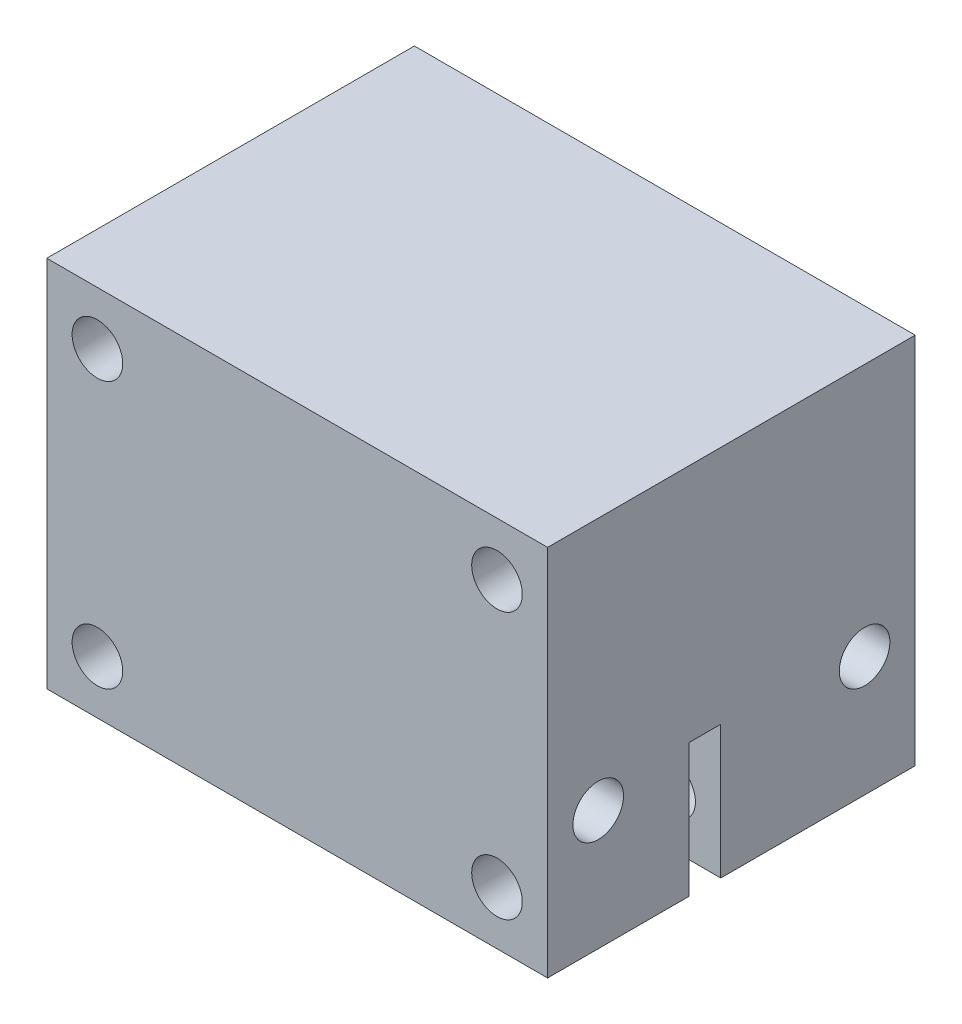
SolidWorks part; units mm, degrees
material "PBT 一般用途"
ref_plane "前视基准面" through (0, 0, 0) normal (0, 0, 1) x (1, 0, 0)
ref_plane "上视基准面" through (0, 0, 0) normal (0, 1, 0) x (1, 0, 0)
ref_plane "右视基准面" through (0, 0, 0) normal (1, 0, 0) x (0, 0, -1)
sketch "草图1" plane through (0, 0, 0) normal (0, 0, 1) x (1, 0, 0)
  line L0 (18.8, 28) -> (18.8, 0) construction
  line L1 (0, 0) -> (37.6, 0)
  line L2 (0, 0) -> (0, 28)
  line L3 (0, 28) -> (37.6, 28)
  line L4 (37.6, 0) -> (37.6, 28)
  line L6 (3.8, 4) -> (33.8, 4) construction
  line L7 (3.8, 4) -> (3.8, 24) construction
  line L8 (3.8, 24) -> (33.8, 24) construction
  line L9 (33.8, 4) -> (33.8, 24) construction
  line L10 (3.8, 4) -> (33.8, 24) construction
  line L11 (3.8, 24) -> (33.8, 4) construction
  circle A0 centre (3.8, 24) radius 1.9
  circle A1 centre (33.8, 24) radius 1.9
  circle A2 centre (33.8, 4) radius 1.9
  circle A3 centre (3.8, 4) radius 1.9
  point P7 (18.8, 14)
  dimension "D3" = 20
  dimension "D5" = 3.8
  dimension "D1" = 28
  dimension "D2" = 37.6
  dimension "D4" = 30
extrude "凸台-拉伸1" add sketch "草图1" along normal blind 27.6
sketch "草图2" plane through (37.6, 0, 0) normal (1, 0, 0) x (0, 0, -1)
  line L0 (-13.8, 28) -> (-13.8, 0) construction
  line L1 (-27.6, 28) -> (0, 28) construction
  line L2 (-27.6, 0) -> (0, 0) construction
  line L3 (-23.8, 9) -> (-3.8, 9) construction
  line L4 (-27.6, 0) -> (-27.6, 28) construction
  line L5 (-17, 0) -> (-14.6, 0)
  line L6 (-17, 0) -> (-17, 10)
  line L7 (-17, 10) -> (-14.6, 10)
  line L8 (-14.6, 0) -> (-14.6, 10)
  circle A0 centre (-23.8, 9) radius 1.9
  circle A1 centre (-3.8, 9) radius 1.9
  point P8 (-13.8, 9)
  dimension "D3" = 3.8
  dimension "D1" = 9
  dimension "D2" = 20
  dimension "D4" = 2.4
  dimension "D5" = 10.6
  dimension "D6" = 10
extrude "切除-拉伸1" cut sketch "草图2" against normal through all
